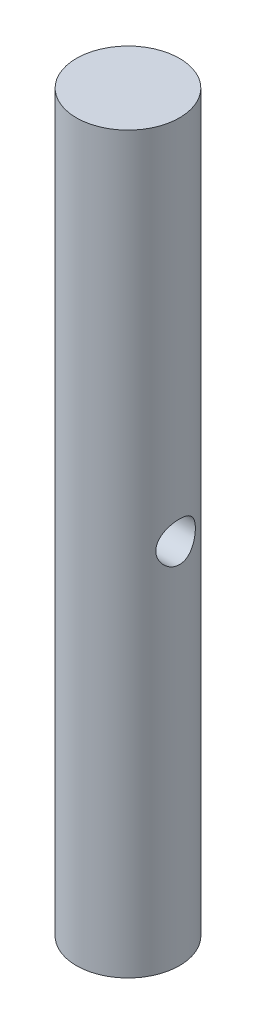
SolidWorks part; units mm, degrees
ref_plane "Front Plane" through (0, 0, 0) normal (0, 0, 1) x (1, 0, 0)
ref_plane "Top Plane" through (0, 0, 0) normal (0, 1, 0) x (1, 0, 0)
ref_plane "Right Plane" through (0, 0, 0) normal (1, 0, 0) x (0, 0, -1)
sketch "Sketch1" plane through (0, 0, 0) normal (0, 1, 0) x (1, 0, 0)
  circle A0 centre (0, 0) radius 4.5625
  dimension "D1" = 9.125
extrude "Boss-Extrude1" add sketch "Sketch1" along normal blind 65
sketch "Sketch2" plane through (0, 0, 0) normal (1, 0, 0) x (0, 0, -1)
  line L0 (4.5625, 65) -> (-4.5625, 65) construction
  circle A0 centre (0, 32.5) radius 1.75
  dimension "D1" = 0
  dimension "D2" = 3.5
  dimension "D3" = 32.5
extrude "Cut-Extrude1" cut sketch "Sketch2" against normal through all and the other way through all
sketch "Sketch4" plane through (0, 0, 0) normal (0, -1, 0) x (-1, 0, 0)
  line L0 (-2.4559, -2.315) -> (-2.4559, 2.315)
  line L1 (0, 0) -> (-2.4559, 0) construction
  arc A0 (-2.4559, -2.315) -> (-2.4559, 2.315) centre (0, 0) ccw
  dimension "D1" = 6.75
  dimension "D2" = 4.63
extrude "Cut-Extrude2" cut sketch "Sketch4" against normal blind 23.5
